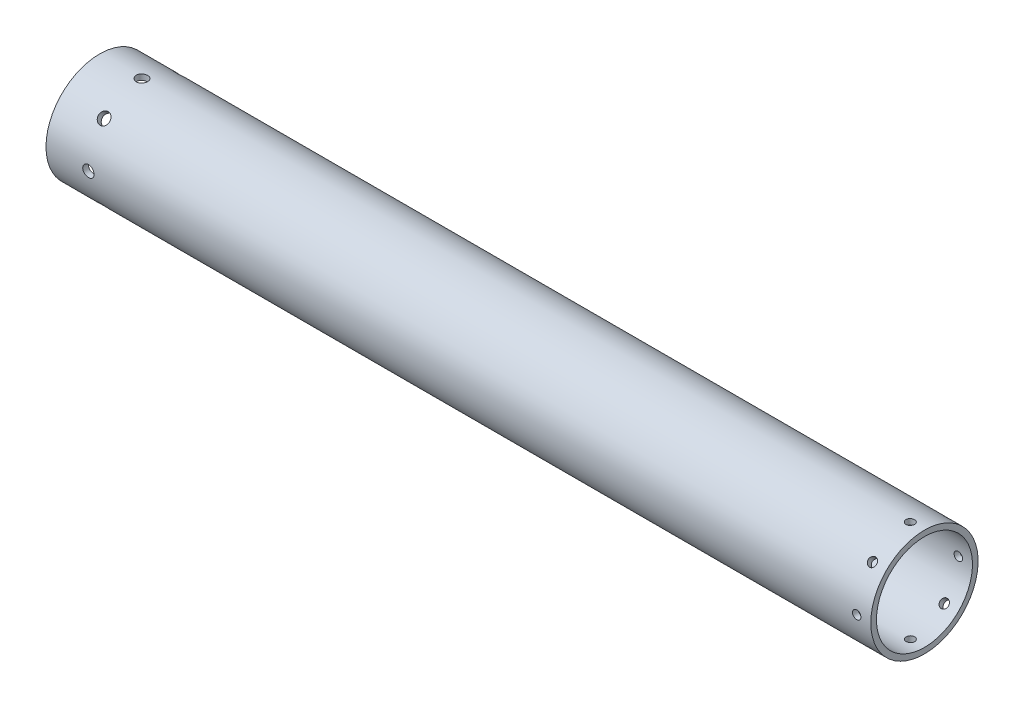
SolidWorks part; units mm, degrees
ref_plane "Front Plane" through (0, 0, 0) normal (0, 0, 1) x (1, 0, 0)
ref_plane "Top Plane" through (0, 0, 0) normal (0, 1, 0) x (1, 0, 0)
ref_plane "Right Plane" through (0, 0, 0) normal (1, 0, 0) x (0, 0, -1)
sketch "Sketch1" plane through (0, 0, 0) normal (0, 0, 1) x (1, 0, 0)
  line L0 (-46.7328, 0) -> (38.1246, 0) construction
  line L2 (0, -17) -> (292.1, -17)
  line L3 (0, -17) -> (0, -19)
  line L4 (0, -19) -> (292.1, -19)
  line L5 (292.1, -17) -> (292.1, -19)
  dimension "D1" = 17
  dimension "D2" = 19
  dimension "D3" = 292.1
revolve "Revolve2" add sketch "Sketch1" angle 360 about L0
sketch "Sketch2" plane through (0, 0, 0) normal (0, 0, 1) x (1, 0, 0)
  line L0 (0, 19) -> (0, -19) construction
  line L1 (292.1, -19) -> (292.1, 19) construction
  circle A0 centre (15, 0) radius 2
  circle A1 centre (287.1, 0) radius 1.5
  point P7 (0, 0)
  dimension "D1" = 4
  dimension "D3" = 3
  dimension "D2" = 15
  dimension "D4" = 5
extrude "Cut-Extrude1" cut sketch "Sketch2" against normal through all
pattern_circular "CirPattern1" count 8 over 360 about axis through (-46.7328, 0, 0) along (-1, 0, 0) of "Cut-Extrude1"
